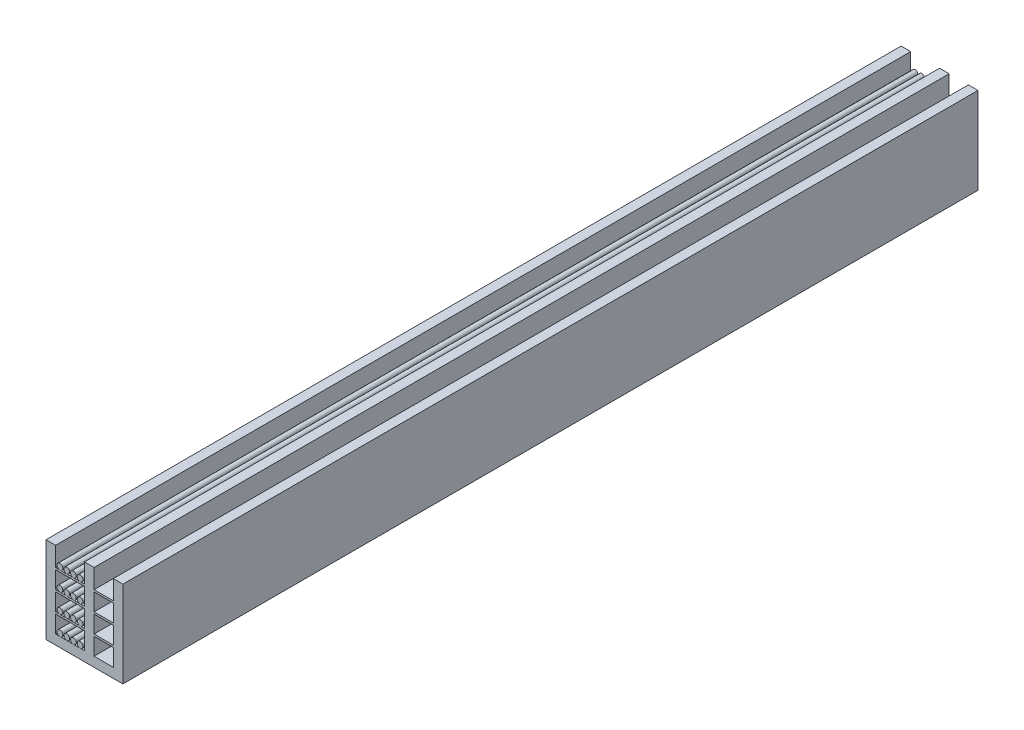
SolidWorks part; units mm, degrees
ref_plane "Alzado" through (0, 0, 0) normal (0, 0, 1) x (1, 0, 0)
ref_plane "Planta" through (0, 0, 0) normal (0, 1, 0) x (1, 0, 0)
ref_plane "Vista lateral" through (0, 0, 0) normal (1, 0, 0) x (0, 0, -1)
sketch "Croquis1" plane through (0, 0, 0) normal (0, 0, 1) x (1, 0, 0)
  line L0 (0, 0) -> (-800, 0)
  line L1 (-800, 0) -> (-800, 600)
  line L2 (-800, 600) -> (-700, 600)
  line L3 (-700, 600) -> (-700, 100)
  line L4 (-700, 100) -> (-400, 100)
  line L5 (-400, 100) -> (-400, 470)
  line L6 (-400, 470) -> (-300, 470)
  line L7 (-300, 470) -> (-300, 100)
  line L8 (-300, 100) -> (-100, 100)
  line L9 (-100, 100) -> (-100, 600)
  line L10 (-100, 600) -> (0, 600)
  line L11 (0, 600) -> (0, 0)
  dimension "D1" = 800
  dimension "D2" = 600
  dimension "D3" = 100
  dimension "D4" = 500
  dimension "D5" = 300
  dimension "D6" = 370
  dimension "D7" = 100
  dimension "D8" = 370
  dimension "D9" = 200
extrude "Saliente-Extruir1" add sketch "Croquis1" along normal blind 8900
sketch "Croquis2" plane through (0, 0, 0) normal (0, 0, -1) x (-1, 0, 0)
  line L0 (300, 470) -> (300, 600)
  line L1 (300, 600) -> (400, 600)
  line L2 (400, 600) -> (400, 470)
  line L3 (400, 470) -> (300, 470)
extrude "Saliente-Extruir2" add sketch "Croquis2" against normal up to surface (8900 mm away) up to face at (-383.3333, 311.6667, 8900)
sketch "Croquis3" plane through (0, 0, 0) normal (0, 0, -1) x (-1, 0, 0)
  line L0 (100, 600) -> (100, 900)
  line L1 (100, 900) -> (0, 900)
  line L2 (0, 900) -> (0, 600)
  line L3 (0, 600) -> (100, 600)
  line L4 (300, 600) -> (300, 900)
  line L5 (300, 900) -> (400, 900)
  line L6 (400, 900) -> (400, 600)
  line L7 (400, 600) -> (300, 600)
  line L8 (700, 600) -> (700, 900)
  line L9 (700, 900) -> (800, 900)
  line L10 (800, 900) -> (800, 600)
  line L11 (800, 600) -> (700, 600)
extrude "Saliente-Extruir3" add sketch "Croquis3" against normal up to surface (8900 mm away) up to face at (-383.3333, 333.3333, 8900)
sketch "Croquis4" plane through (-800, 0, 0) normal (-1, 0, 0) x (0, 0, 1)
  line L1 (0, 900) -> (0, 0) construction
  line L3 (0, 280) -> (8900, 280)
  line L4 (0, 280) -> (0, 300)
  line L5 (0, 300) -> (8900, 300)
  line L7 (0, 480) -> (8900, 480)
  line L8 (0, 480) -> (0, 500)
  line L9 (0, 500) -> (8900, 500)
  line L11 (0, 680) -> (8900, 680)
  line L12 (0, 680) -> (0, 700)
  line L13 (0, 700) -> (8900, 700)
  line L14 (8900, 700) -> (8900, 680)
  line L15 (8900, 300) -> (8900, 280)
  line L16 (8900, 500) -> (8900, 480)
  dimension "D3" = 20
  dimension "D4" = 180
  dimension "D5" = 20
  dimension "D6" = 180
  dimension "D7" = 20
extrude "Saliente-Extruir4" add sketch "Croquis4" against normal up to surface (700 mm away) up to face at (-100, 500, 4450)
sketch "Croquis6" plane through (0, 0, 0) normal (0, 0, -1) x (-1, 0, 0)
  line L0 (400, 100) -> (700, 100) construction
  line L1 (400, 280) -> (400, 100) construction
  circle A0 centre (445, 130) radius 30
  circle A1 centre (515, 130) radius 30
  circle A2 centre (585, 130) radius 30
  circle A3 centre (655, 130) radius 30
  dimension "D1" = 60
  dimension "D2" = 60
  dimension "D3" = 60
  dimension "D4" = 60
  dimension "D9" = 70
  dimension "D10" = 70
  dimension "D11" = 70
  dimension "D5" = 30
  dimension "D6" = 30
  dimension "D7" = 30
  dimension "D8" = 30
  dimension "D12" = 45
extrude "Saliente-Extruir5" add sketch "Croquis6" against normal up to surface (8900 mm away) separate body up to face at (-383.3333, 683.3333, 8900)
pattern_linear "MatrizL1" count 4 spacing 200 along (0, 1, 0) of "Saliente-Extruir5"
